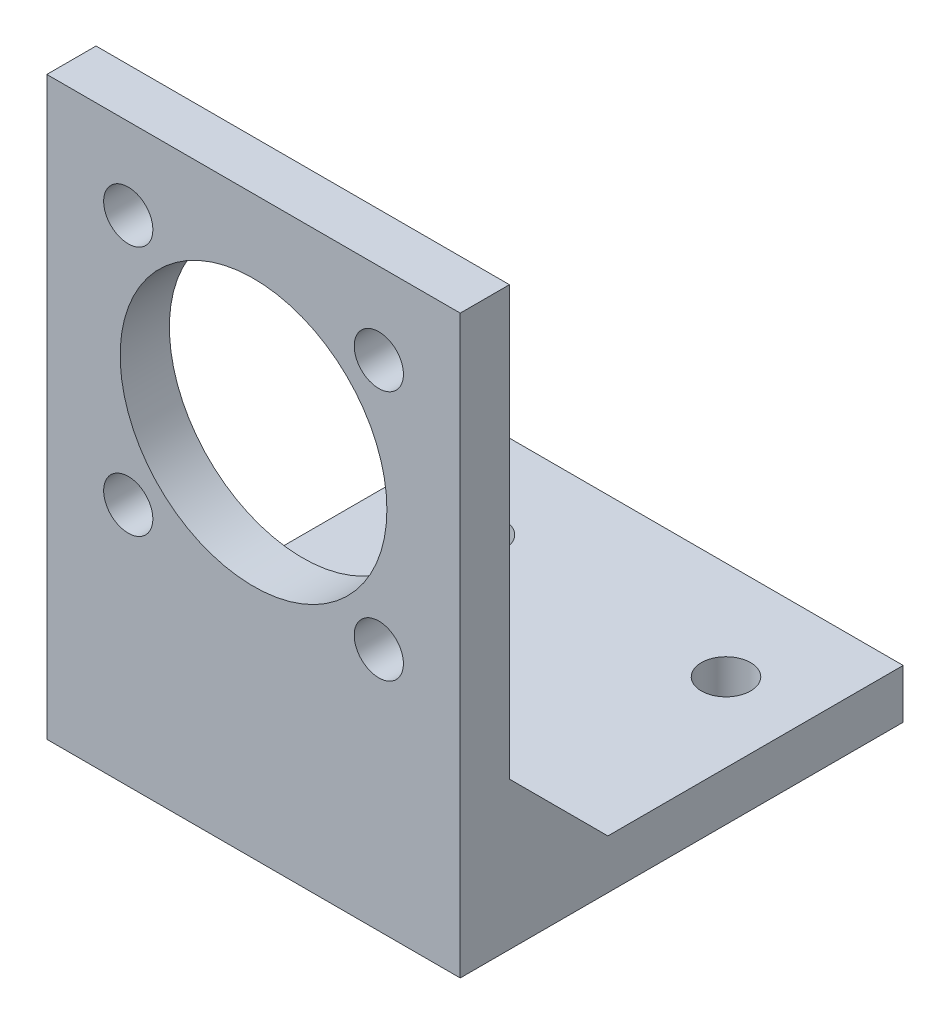
SolidWorks part; units mm, degrees
ref_plane "前视基准面" through (0, 0, 0) normal (0, 0, 1) x (1, 0, 0)
ref_plane "上视基准面" through (0, 0, 0) normal (0, 1, 0) x (1, 0, 0)
ref_plane "右视基准面" through (0, 0, 0) normal (1, 0, 0) x (0, 0, -1)
sketch "草图1" plane through (0, 0, 0) normal (0, 1, 0) x (0, 0, -1)
  line L1 (0, 0) -> (-40, 0)
  line L2 (0, 0) -> (0, 42)
  line L3 (0, 42) -> (-40, 42)
  line L4 (-40, 0) -> (-40, 42)
  circle A0 centre (-10, 33) radius 2.5
  circle A1 centre (-10, 8) radius 2.5
  dimension "D3" = 25
  dimension "D4" = 5
  dimension "D5" = 8
  dimension "D1" = 42
  dimension "D2" = 40
  dimension "D6" = 10
extrude "凸台-拉伸1" add sketch "草图1" along normal blind 5
sketch "草图2" plane through (0, 0, 40) normal (0, 0, 1) x (1, 0, 0)
  line L0 (0, 5) -> (0, 0) construction
  line L5 (-42, 0) -> (0, 0)
  line L6 (-42, 0) -> (-42, 58.5)
  line L7 (-42, 58.5) -> (0, 58.5)
  line L8 (0, 0) -> (0, 58.5)
  line L9 (-33.7279, 24.7721) -> (-8.2721, 50.2279) construction
  circle A0 centre (-21, 37.5) radius 13.55
  circle A5 centre (-33.7279, 24.7721) radius 2.5
  circle A6 centre (-8.2721, 50.2279) radius 2.5
  circle A7 centre (-33.7279, 50.2279) radius 2.5
  circle A8 centre (-8.2721, 24.7721) radius 2.5
  point P11 (-21, 0)
  point P12 (-21, 37.5)
  point P25 (-21, 58.5)
  dimension "D1" = 37.5
  dimension "D2" = 27.1
  dimension "D4" = 36
  dimension "D5" = 5
  dimension "D3" = 58.5
  dimension "D6" = 45
extrude "凸台-拉伸2" add sketch "草图2" along normal blind 5
sketch "草图3" plane through (0, 0, 0) normal (1, 0, 0) x (0, 0, -1)
  line L0 (-40, 15) -> (-40, 5)
  line L1 (-40, 5) -> (-40, 58.5) construction
  line L2 (-40, 5) -> (-30, 5)
  line L3 (-40, 5) -> (0, 5) construction
  line L4 (-30, 5) -> (-40, 15)
  dimension "D1" = 10
extrude "凸台-拉伸3" add sketch "草图3" against normal blind 5
pattern_linear "阵列(线性)1" count 2 spacing 37 along (-1, 0, 0) of "凸台-拉伸3"
